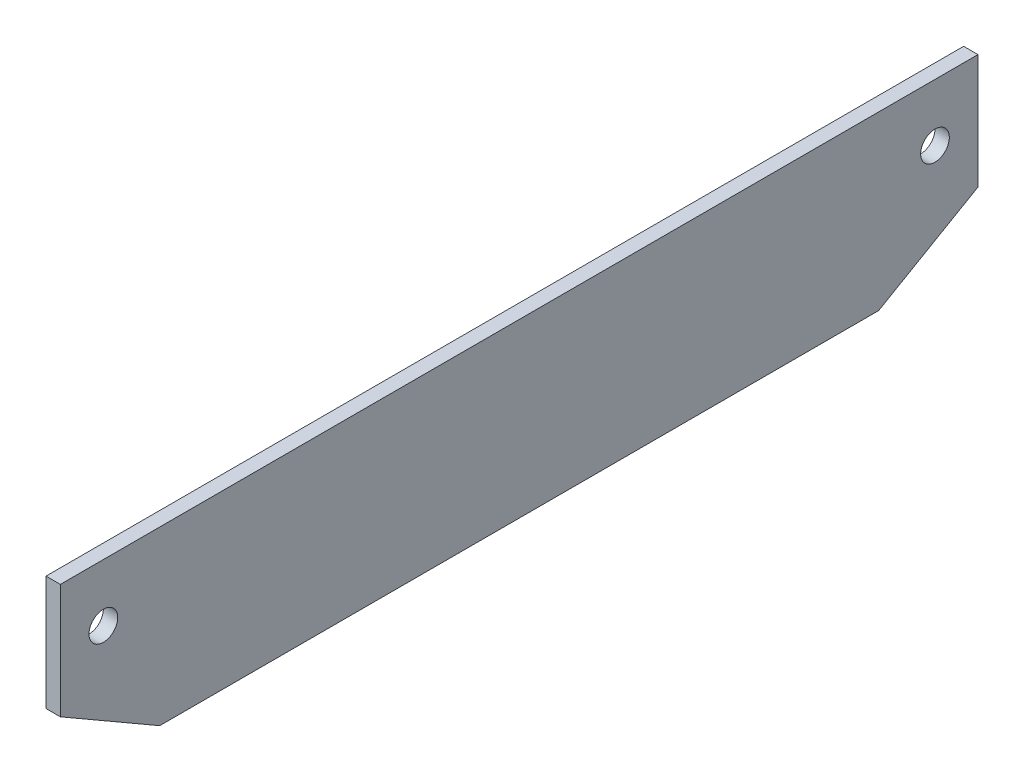
SolidWorks part; units mm, degrees
ref_plane "Front Plane" through (0, 0, 0) normal (0, 0, 1) x (1, 0, 0)
ref_plane "Top Plane" through (0, 0, 0) normal (0, 1, 0) x (1, 0, 0)
ref_plane "Right Plane" through (0, 0, 0) normal (1, 0, 0) x (0, 0, -1)
sketch "Sketch1" plane through (0, 0, 0) normal (1, 0, 0) x (0, 0, -1)
  line L0 (-92.075, 0) -> (-101.6, 0) construction
  line L1 (-101.6, -12.7) -> (101.6, -12.7) construction
  line L2 (-101.6, -12.7) -> (-101.6, 12.7)
  line L3 (-101.6, 12.7) -> (101.6, 12.7)
  line L4 (101.6, -12.7) -> (101.6, 12.7)
  line L5 (-101.6, -12.7) -> (101.6, 12.7) construction
  line L6 (-101.6, 12.7) -> (101.6, -12.7) construction
  line L7 (92.075, 0) -> (101.6, 0) construction
  line L8 (101.6, -12.7) -> (79.603, -25.4)
  line L9 (0, -12.7) -> (0, -51.163) construction
  line L10 (79.603, -25.4) -> (-79.603, -25.4)
  line L11 (-101.6, -12.7) -> (-79.603, -25.4)
  circle A0 centre (-92.075, 0) radius 3.175
  circle A1 centre (92.075, 0) radius 3.175
  point P0 (0, 0)
  point P17 (0, -25.4)
  dimension "D3" = 6.35
  dimension "D1" = 25.4
  dimension "D2" = 203.2
  dimension "D4" = 9.525
  dimension "D5" = 12.7
  dimension "D6" = 30
extrude "Boss-Extrude1" add sketch "Sketch1" along normal blind 3.175
